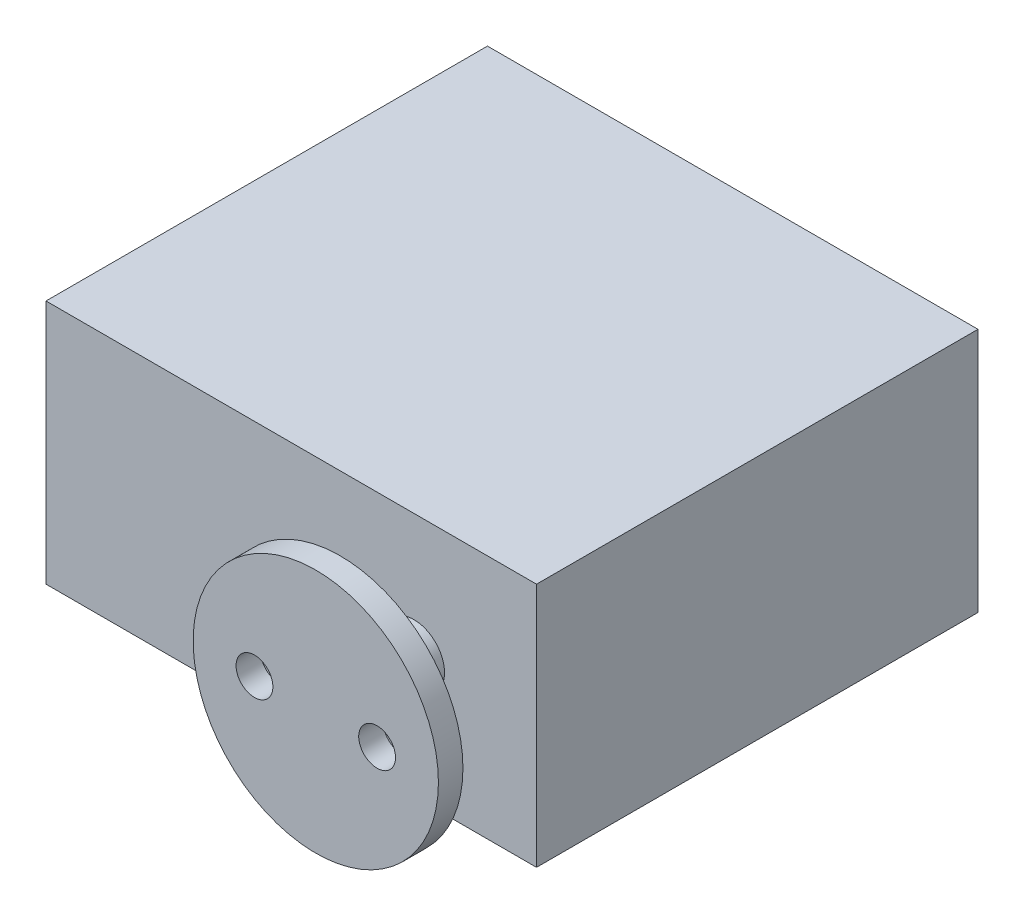
SolidWorks part; units mm, degrees
ref_plane "Спереди" through (0, 0, 0) normal (0, 0, 1) x (1, 0, 0)
ref_plane "Сверху" through (0, 0, 0) normal (0, 1, 0) x (1, 0, 0)
ref_plane "Справа" through (0, 0, 0) normal (1, 0, 0) x (0, 0, -1)
sketch "Эскиз1" plane through (0, 0, 0) normal (0, 0, 1) x (1, 0, 0)
  line L1 (20, 10) -> (-20, 10)
  line L2 (20, 10) -> (20, -10)
  line L3 (20, -10) -> (-20, -10)
  line L4 (-20, 10) -> (-20, -10)
  line L5 (20, 10) -> (-20, -10) construction
  line L6 (20, -10) -> (-20, 10) construction
  point P0 (0, 0)
  dimension "D1" = 40
  dimension "D2" = 20
extrude "Бобышка-Вытянуть1" add sketch "Эскиз1" along normal blind 36
sketch "Эскиз2" plane through (0, 0, 36) normal (0, 0, 1) x (1, 0, 0)
  line L0 (-20, 0) -> (20, 0) construction
  line L1 (-20, 10) -> (-20, -10) construction
  line L2 (20, -10) -> (20, 10) construction
  circle A0 centre (10, 0) radius 2.5
  dimension "D1" = 10
  dimension "D2" = 5
extrude "Бобышка-Вытянуть2" add sketch "Эскиз2" along normal blind 6
sketch "Эскиз4" plane through (0, 0, 42) normal (0, 0, 1) x (1, 0, 0)
  line L0 (0, 0) -> (20, 0) construction
  circle A0 centre (10, 0) radius 10
  circle A1 centre (5, 0) radius 1.5
  circle A2 centre (15, 0) radius 1.5
  dimension "D1" = 3
  dimension "D2" = 20
  dimension "D4" = 5
  dimension "D3" = 5
extrude "Бобышка-Вытянуть3" add sketch "Эскиз4" along normal blind 2
